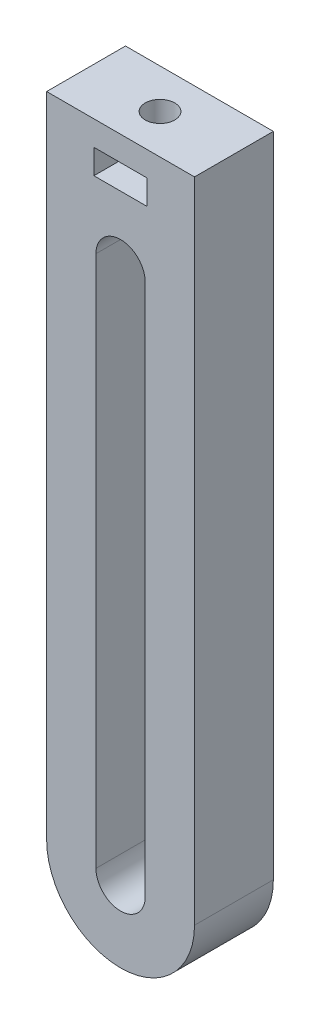
SolidWorks part; units mm, degrees
material "PLA Density Only"
ref_plane "Front Plane" through (0, 0, 0) normal (0, 0, 1) x (1, 0, 0)
ref_plane "Top Plane" through (0, 0, 0) normal (0, 1, 0) x (1, 0, 0)
ref_plane "Right Plane" through (0, 0, 0) normal (1, 0, 0) x (0, 0, -1)
sketch "Sketch1" plane through (0, 0, 0) normal (0, 0, 1) x (1, 0, 0)
  line L0 (0, 27) -> (0, -27) construction
  line L1 (2.5, 27) -> (2.5, -27)
  line L2 (-2.5, 27) -> (-2.5, -27)
  line L7 (-7.5, 38.75) -> (7.5, 38.75)
  line L8 (-7.5, 38.75) -> (-7.5, -27)
  line L10 (7.5, -27) -> (7.5, 38.75)
  arc A0 (2.5, 27) -> (-2.5, 27) centre (0, 27) ccw
  arc A1 (-2.5, -27) -> (2.5, -27) centre (0, -27) ccw
  arc A4 (7.5, -27) -> (-7.5, -27) centre (0, -27) cw
  point P2 (0, 0)
  point P11 (0, 38.75)
  dimension "D3" = 2.5
  dimension "D1" = 11.75
  dimension "D2" = 54
  dimension "D4" = 15
extrude "Boss-Extrude1" add sketch "Sketch1" along normal blind 8
sketch "Sketch3" plane through (0, 38.75, 0) normal (0, 1, 0) x (1, 0, 0)
  line L0 (7.5, 0) -> (-7.5, 0) construction
  line L1 (0, -7.1235) -> (2.705, -5.5617)
  line L2 (2.705, -5.5617) -> (2.705, -2.4383)
  line L3 (2.705, -2.4383) -> (0, -0.8765)
  line L4 (0, -0.8765) -> (-2.705, -2.4383)
  line L5 (-2.705, -2.4383) -> (-2.705, -5.5617)
  line L6 (-2.705, -5.5617) -> (0, -7.1235)
  circle A0 centre (0, -4) radius 2.705 construction
  dimension "D1" = 5.41
  dimension "D2" = 4
extrude "Cut-Extrude2" cut sketch "Sketch3" against normal blind 2.5 from offset 2.5 offset against normal yes
sketch "Sketch4" plane through (0, 0, 8) normal (0, 0, 1) x (1, 0, 0)
  line L1 (-2.705, 36.25) -> (2.705, 36.25)
  line L2 (-2.705, 36.25) -> (-2.705, 33.75)
  line L3 (-2.705, 33.75) -> (2.705, 33.75)
  line L4 (2.705, 36.25) -> (2.705, 33.75)
  line L5 (-2.705, 36.25) -> (2.705, 33.75) construction
  line L6 (-2.705, 33.75) -> (2.705, 36.25) construction
  line L7 (7.5, 38.75) -> (-7.5, 38.75) construction
  point P0 (0, 35)
  dimension "D1" = 2.5
  dimension "D2" = 5.41
  dimension "D3" = 2.5
extrude "Cut-Extrude3" cut sketch "Sketch4" against normal blind 4
sketch "Sketch5" plane through (0, 38.75, 0) normal (0, 1, 0) x (1, 0, 0)
  line L0 (7.5, 0) -> (-7.5, 0) construction
  circle A0 centre (0, -4) radius 1.5
  dimension "D1" = 3
  dimension "D2" = 4
extrude "Cut-Extrude4" cut sketch "Sketch5" against normal up to surface (9.25 mm away)
